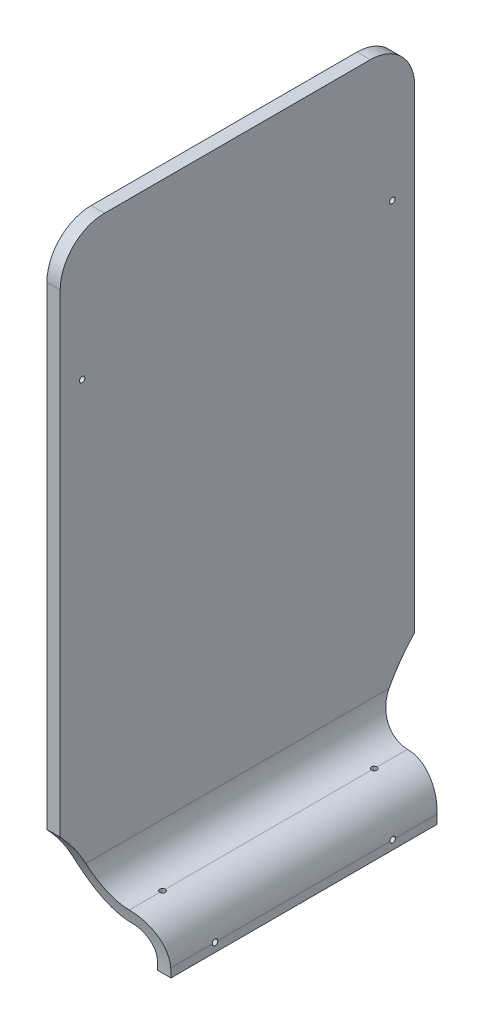
SolidWorks part; units mm, degrees
ref_plane "Front Plane" through (0, 0, 0) normal (0, 0, 1) x (1, 0, 0)
ref_plane "Top Plane" through (0, 0, 0) normal (0, 1, 0) x (1, 0, 0)
ref_plane "Right Plane" through (0, 0, 0) normal (1, 0, 0) x (0, 0, -1)
sketch "Sketch1" plane through (0, 0, 0) normal (0, 0, 1) x (1, 0, 0)
  line L0 (0, 0) -> (0, 5.08)
  line L1 (-38.1, 43.18) -> (-38.1, 360.68)
  arc A0 (0, 5.08) -> (-12.7, 17.78) centre (-12.7, 5.08) ccw
  arc A1 (-12.7, 17.78) -> (-38.1, 43.18) centre (-12.7, 43.18) cw
extrude "Extrude-Thin1" add sketch "Sketch1" along normal mid plane 203.2 thin
fillet "Fillet1" radius 25.4 1 edges at (-34.29, 360.68, 101.6)
fillet "Fillet2" radius 25.4 1 edges at (-34.29, 360.68, -101.6)
sketch3d "3DSketch1"
  point P0 (7.62, 3.3151, 74.6375)
ref_plane "Plane1" through (7.62, 0, 0) normal (1, 0, 0) x (0, 0, -1)
sketch "Sketch3" plane through (7.62, 0, 0) normal (1, 0, 0) x (0, 0, -1)
  line L0 (-101.6, 0) -> (-101.6, 63.5333)
  line L1 (-101.6, 43.18) -> (-101.6, 335.28) construction
  line L2 (-101.6, 0) -> (-76.2, 0)
  line L3 (-101.6, 0) -> (101.6, 0) construction
  line L4 (101.6, 0) -> (76.2, 0)
  line L5 (101.6, 0) -> (101.6, 63.5333)
  line L6 (101.6, 43.18) -> (101.6, 335.28) construction
  arc A0 (-76.2, 0) -> (-101.6, 63.5333) centre (-168.3583, 0) ccw
  arc A1 (76.2, 0) -> (101.6, 63.5333) centre (168.3583, 0) cw
extrude "Cut-Extrude1" cut sketch "Sketch3" against normal blind 54.61 and the other way blind 10.922
sketch3d "3DSketch2"
  point P0 (-30.48, 283.6815, 28.2424)
ref_plane "Plane2" through (-30.48, 0, 0) normal (1, 0, 0) x (0, 0, -1)
sketch "Sketch4" plane through (-30.48, 0, 0) normal (1, 0, 0) x (0, 0, -1)
  circle A1 centre (-89.0039, 284.48) radius 1.5875
  circle A2 centre (88.8038, 284.48) radius 1.5875
extrude "Cut-Extrude2" cut sketch "Sketch4" against normal blind 17.78 and the other way blind 14.224
sketch3d "3DSketch3"
  line L0 (-12.7, 25.4, 79.7694) -> (-12.7, 25.4, -79.7694) construction
  point P0 (-12.7, 25.4, -8.0832)
sketch3d "3DSketch4"
  line L0 (-12.7, 25.4, 79.7694) -> (-12.7, 25.4, -79.7694) construction
  point P0 (-12.7, 25.4, 5.2197)
ref_plane "Plane4" through (0, 25.4, 0) normal (0, 1, 0) x (1, 0, 0)
sketch "Sketch5" plane through (0, 25.4, 0) normal (0, 1, 0) x (1, 0, 0)
  line L1 (-12.7, -79.7694) -> (-12.7, 79.7694) construction
  circle A0 centre (-12.7, -60.7194) radius 1.5875
  circle A1 centre (-12.7, 60.7194) radius 1.5875
extrude "Cut-Extrude3" cut sketch "Sketch5" against normal blind 23.876 and the other way blind 14.732
sketch3d "3DSketch5"
  point P0 (7.62, 3.3151, -30.6205)
ref_plane "Plane5" through (7.62, 0, 0) normal (1, 0, 0) x (0, 0, -1)
sketch "Sketch6" plane through (7.62, 0, 0) normal (1, 0, 0) x (0, 0, -1)
  line L1 (-76.3401, 5.08) -> (76.3401, 5.08) construction
  circle A0 centre (-50.9401, 5.08) radius 1.5875
  circle A1 centre (50.9401, 5.08) radius 1.5875
extrude "Cut-Extrude5" cut sketch "Sketch6" against normal blind 39.37 and the other way blind 15.24
